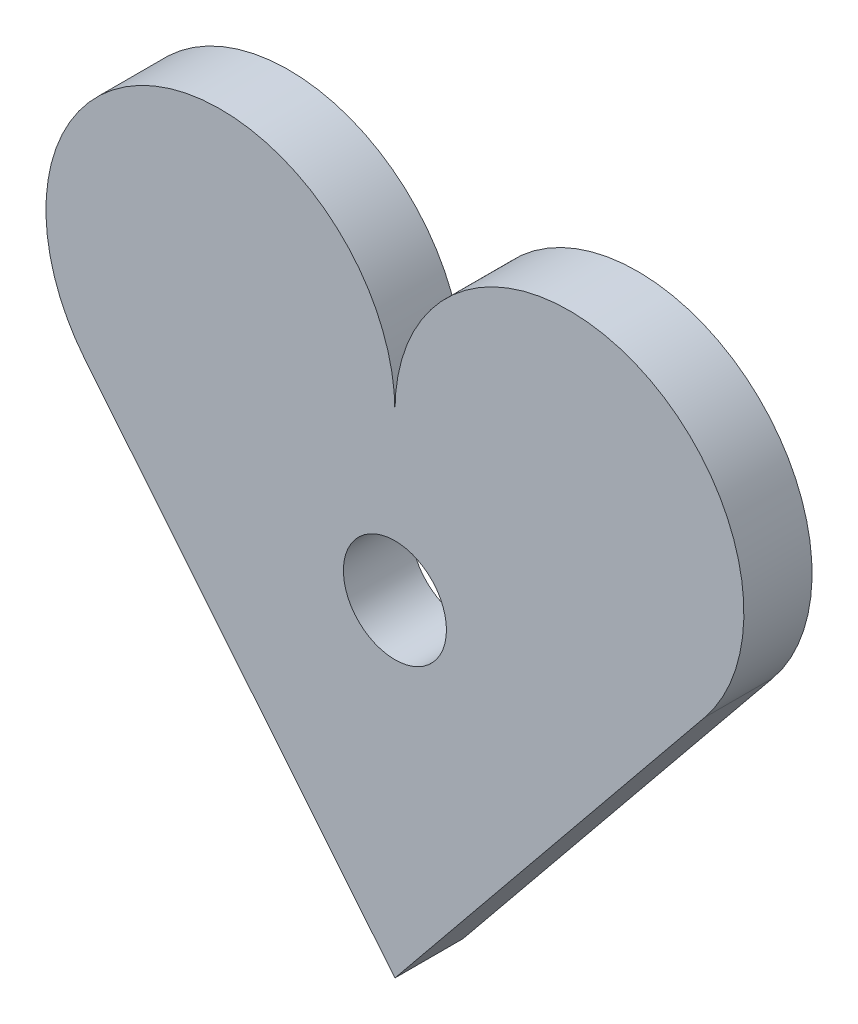
SolidWorks part; units mm, degrees
ref_plane "Front Plane" through (0, 0, 0) normal (0, 0, 1) x (1, 0, 0)
ref_plane "Top Plane" through (0, 0, 0) normal (0, 1, 0) x (1, 0, 0)
ref_plane "Right Plane" through (0, 0, 0) normal (1, 0, 0) x (0, 0, -1)
sketch "Sketch1" plane through (0, 0, 0) normal (0, 0, 1) x (1, 0, 0)
  line L0 (-6.5803, 85.7468) -> (7.8513, 68.018)
  line L1 (7.8513, 68.018) -> (22.2828, 85.7468)
  arc A0 (-6.5803, 85.7468) -> (7.8513, 90.878) centre (-0.2767, 90.878) cw
  arc A1 (7.8513, 90.878) -> (22.2828, 85.7468) centre (15.9793, 90.878) cw
  circle A2 centre (7.8513, 83.258) radius 2.4
  point P5 (0, 0)
  point P7 (0, 0)
  point P8 (0, 0)
  point P9 (7.8513, 84.547)
  dimension "D1" = 22.86
  dimension "D2" = 8.128
  dimension "D3" = 4.8
  dimension "D4" = 15.24
extrude "Boss-Extrude1" add sketch "Sketch1" along normal blind 3.175 from offset 7.62
